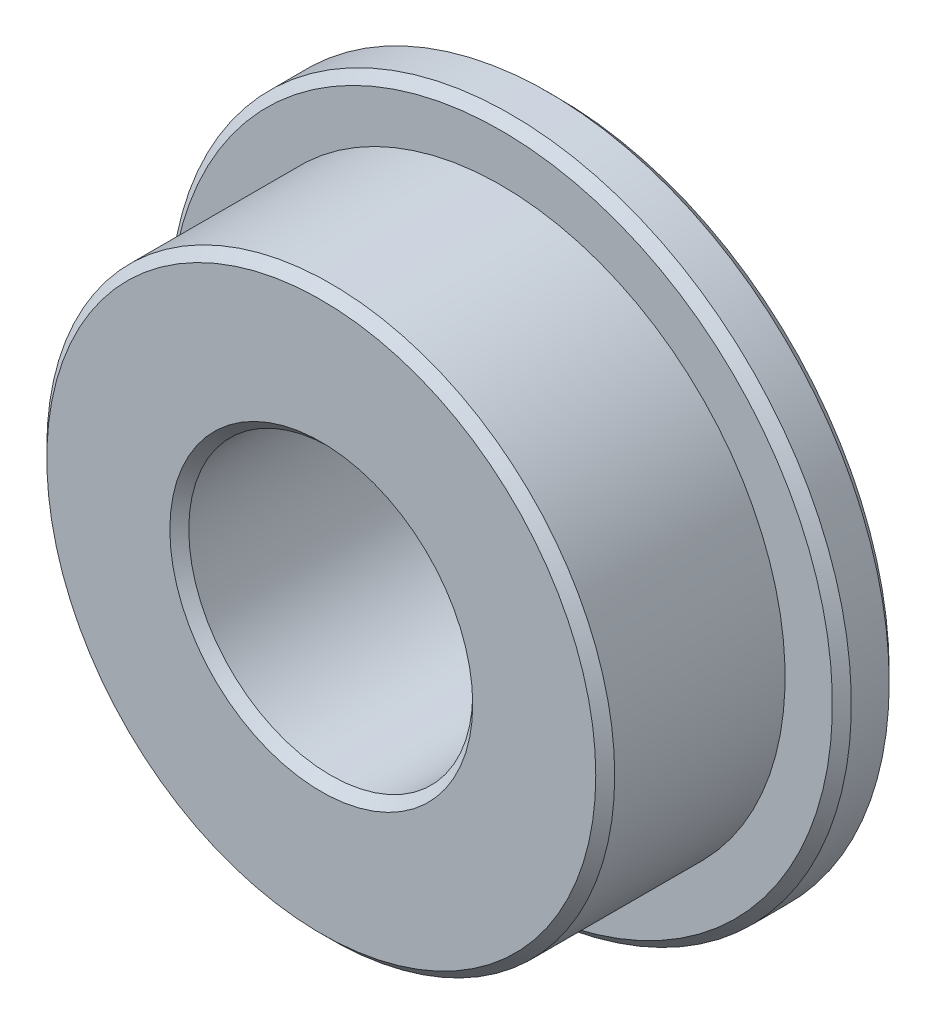
SolidWorks part; units mm, degrees
ref_plane "前视基准面" through (0, 0, 0) normal (0, 0, 1) x (1, 0, 0)
ref_plane "上视基准面" through (0, 0, 0) normal (0, 1, 0) x (1, 0, 0)
ref_plane "右视基准面" through (0, 0, 0) normal (1, 0, 0) x (0, 0, -1)
sketch "草图1" plane through (0, 0, 0) normal (0, 0, 1) x (1, 0, 0)
  circle A0 centre (0, 0) radius 3
  circle A1 centre (0, 0) radius 1.5
  dimension "D1" = 3
  dimension "D2" = 6
extrude "凸台-拉伸1" add sketch "草图1" along normal mid plane 2.5
sketch "草图2" plane through (0, 0, -1.25) normal (0, 0, -1) x (-1, 0, 0)
  circle A0 centre (0, 0) radius 3.6
  circle A1 centre (0, 0) radius 3 construction
  circle A2 centre (0, 0) radius 3
  dimension "D1" = 7.2
extrude "凸台-拉伸2" add sketch "草图2" against normal blind 0.6
chamfer "倒角1" distance 0.1 angle 45 5 edges at (1.5, 0, -1.25) (1.5, 0, 1.25) (3, 0, 1.25) (-3.6, 0, -0.65) (-3.6, 0, -1.25)
